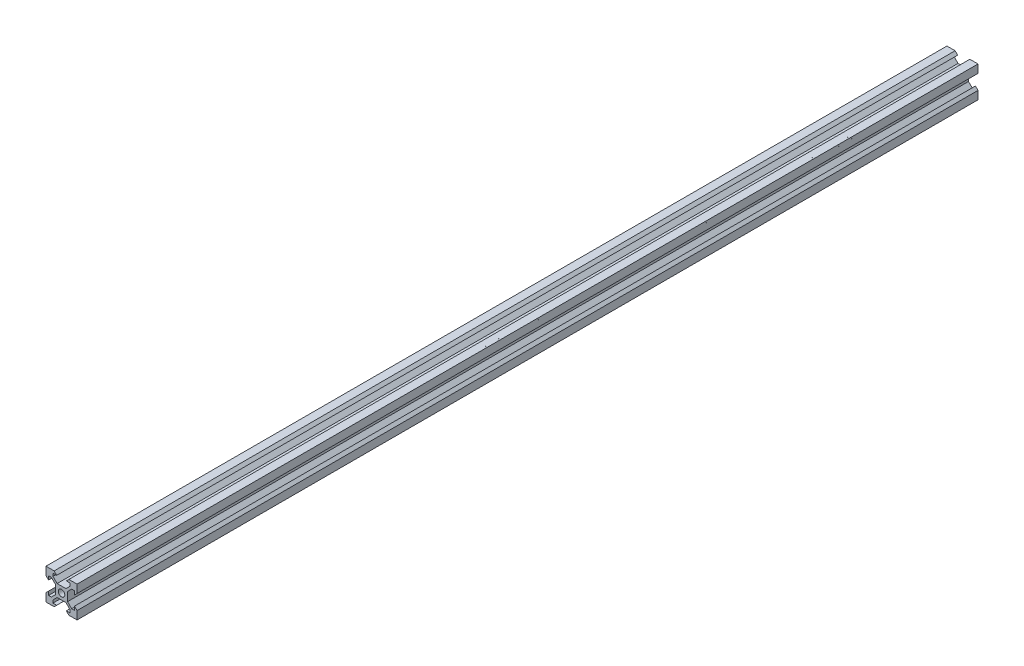
SolidWorks part; units mm, degrees
material "6061-T6 (SS)"
ref_plane "Front Plane" through (0, 0, 0) normal (0, 0, 1) x (1, 0, 0)
ref_plane "Top Plane" through (0, 0, 0) normal (0, 1, 0) x (1, 0, 0)
ref_plane "Right Plane" through (0, 0, 0) normal (1, 0, 0) x (0, 0, -1)
sketch "Sketch1" plane through (0, 0, 0) normal (0, 0, 1) x (1, 0, 0)
  line L0 (2.8343, 3.894) -> (5.5, 6.5588)
  line L1 (2.8343, -3.894) -> (-2.8343, -3.894)
  line L2 (3.8948, -2.8332) -> (3.8948, 2.8332)
  line L3 (2.8343, 3.894) -> (-2.8343, 3.894)
  line L4 (-3.8948, -2.8332) -> (-3.8948, 2.8332)
  line L5 (3.8994, -3.9006) -> (-3.8994, 3.9006) construction
  line L6 (3.9006, 3.8994) -> (-3.9006, -3.8994) construction
  line L7 (10, 4.747) -> (10, 9.9986)
  line L8 (5.5, 6.5588) -> (5.5, 8.3491)
  line L9 (5.5, 8.3491) -> (3.1, 8.3491)
  line L10 (3.1, 8.3491) -> (4.75, 9.9986)
  line L11 (4.75, 9.9986) -> (10, 9.9986)
  line L12 (8.35, 3.0975) -> (10, 4.747)
  line L13 (8.3507, 5.4975) -> (8.35, 3.0975)
  line L14 (6.5605, 5.498) -> (8.3507, 5.4975)
  line L15 (3.8948, 2.8332) -> (6.5605, 5.498)
  line L16 (0, -55) -> (0, 55) construction
  line L17 (-3.8948, 2.8332) -> (-6.5605, 5.498)
  line L18 (-6.5605, 5.498) -> (-8.3507, 5.4975)
  line L19 (-8.3507, 5.4975) -> (-8.35, 3.0975)
  line L20 (-8.35, 3.0975) -> (-10, 4.747)
  line L21 (-4.75, 9.9986) -> (-10, 9.9986)
  line L22 (-3.1, 8.3491) -> (-4.75, 9.9986)
  line L23 (-5.5, 8.3491) -> (-3.1, 8.3491)
  line L24 (-5.5, 6.5588) -> (-5.5, 8.3491)
  line L25 (-10, 4.747) -> (-10, 9.9986)
  line L26 (-2.8343, 3.894) -> (-5.5, 6.5588)
  line L27 (55, 0) -> (-55, 0) construction
  line L28 (3.8948, -2.8332) -> (6.5605, -5.498)
  line L29 (2.8343, -3.894) -> (5.5, -6.5588)
  line L30 (-3.8948, -2.8332) -> (-6.5605, -5.498)
  line L31 (-2.8343, -3.894) -> (-5.5, -6.5588)
  line L32 (-8.3507, -5.4975) -> (-8.35, -3.0975)
  line L33 (-8.35, -3.0975) -> (-10, -4.747)
  line L34 (8.3507, -5.4975) -> (8.35, -3.0975)
  line L35 (8.35, -3.0975) -> (10, -4.747)
  line L36 (-10, -4.747) -> (-10, -9.9986)
  line L37 (-5.5, -6.5588) -> (-5.5, -8.3491)
  line L38 (-5.5, -8.3491) -> (-3.1, -8.3491)
  line L39 (-3.1, -8.3491) -> (-4.75, -9.9986)
  line L40 (-4.75, -9.9986) -> (-10, -9.9986)
  line L41 (-6.5605, -5.498) -> (-8.3507, -5.4975)
  line L42 (6.5605, -5.498) -> (8.3507, -5.4975)
  line L43 (4.75, -9.9986) -> (10, -9.9986)
  line L44 (3.1, -8.3491) -> (4.75, -9.9986)
  line L45 (5.5, -8.3491) -> (3.1, -8.3491)
  line L46 (5.5, -6.5588) -> (5.5, -8.3491)
  line L47 (10, -4.747) -> (10, -9.9986)
  circle A0 centre (0, 0) radius 2.1
  point P0 (0, 0)
  dimension "D6" = 4.2
  dimension "D1" = 7.8
  dimension "D2" = 20
  dimension "D3" = 11
  dimension "D4" = 9.5
  dimension "D5" = 6.2
  dimension "D7" = 1.5
extrude "Boss-Extrude1" add sketch "Sketch1" along normal mid plane 580
